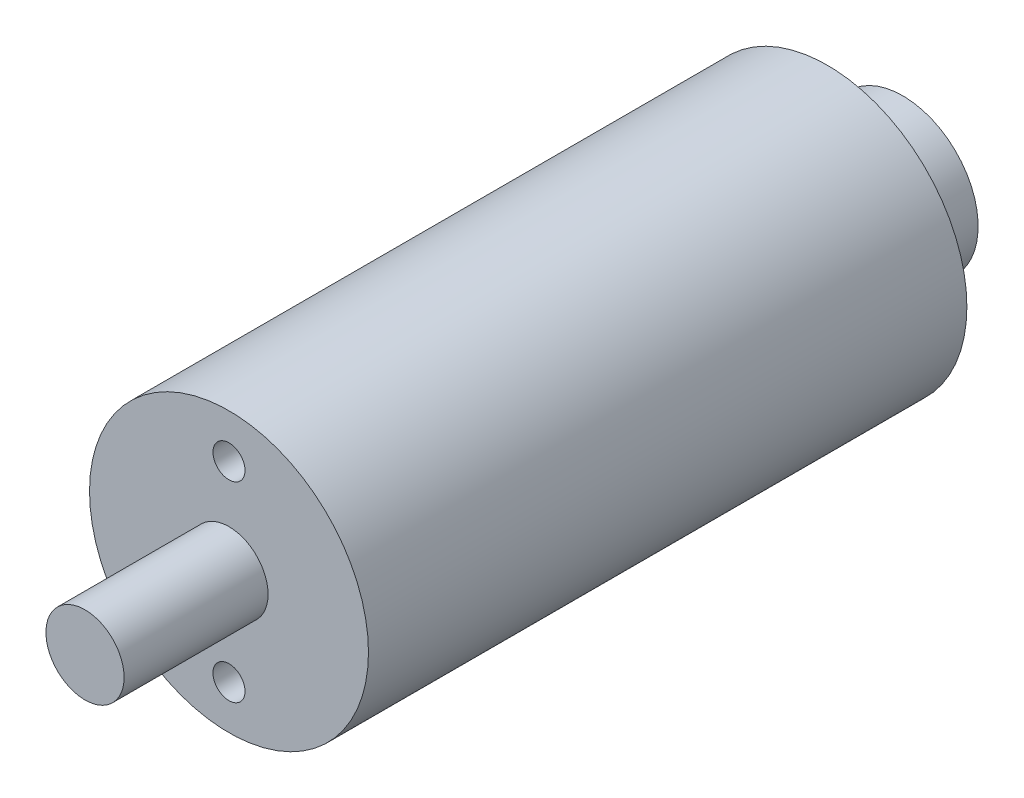
SolidWorks part; units mm, degrees
ref_plane "Front Plane" through (0, 0, 0) normal (0, 0, 1) x (1, 0, 0)
ref_plane "Top Plane" through (0, 0, 0) normal (0, 1, 0) x (1, 0, 0)
ref_plane "Right Plane" through (0, 0, 0) normal (1, 0, 0) x (0, 0, -1)
sketch "Sketch1" plane through (0, 0, 0) normal (0, 0, 1) x (1, 0, 0)
  circle A0 centre (0, 0) radius 12.4
  dimension "D1" = 24.8
extrude "Boss-Extrude1" add sketch "Sketch1" against normal blind 53.2 contours A0
sketch "Sketch2" plane through (0, 0, 0) normal (0, 0, 1) x (1, 0, 0)
  circle A0 centre (0, 0) radius 3.475
  dimension "D1" = 6.95
extrude "Boss-Extrude2" add sketch "Sketch2" along normal blind 12.8 contours A0
sketch "Sketch3" plane through (0, 0, 0) normal (0, 0, 1) x (1, 0, 0)
  line L0 (0, 0) -> (0, 12.4) construction
  line L1 (0, 0) -> (0, -12.4) construction
  circle A0 centre (0, 0) radius 8.5 construction
  circle A1 centre (0, 0) radius 12.4 construction
  circle A2 centre (0, 8.5) radius 1.425
  circle A3 centre (0, -8.5) radius 1.425
  dimension "D1" = 17
  dimension "D2" = 2.85
  dimension "D3" = 2.85
extrude "Cut-Extrude1" cut sketch "Sketch3" against normal blind 5
sketch "Sketch4" plane through (0, 0, -53.2) normal (0, 0, -1) x (-1, 0, 0)
  circle A0 centre (0, 0) radius 6.7
  dimension "D1" = 13.4
extrude "Boss-Extrude3" add sketch "Sketch4" along normal blind 6.7
